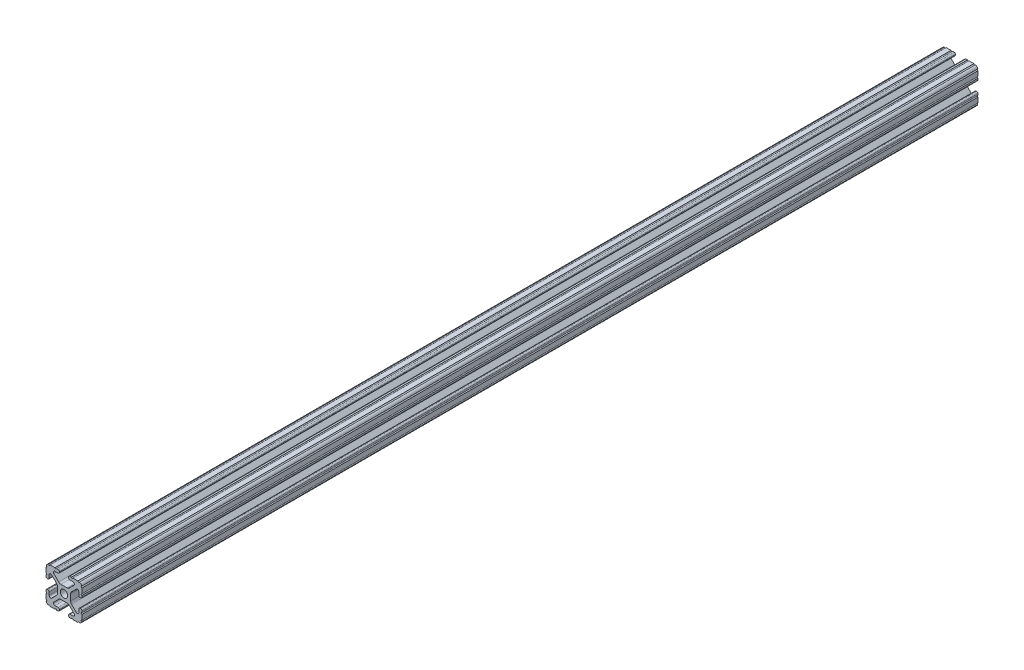
SolidWorks part; units mm, degrees
ref_plane "Front Plane" through (0, 0, 0) normal (0, 0, 1) x (1, 0, 0)
ref_plane "Top Plane" through (0, 0, 0) normal (0, 1, 0) x (1, 0, 0)
ref_plane "Right Plane" through (0, 0, 0) normal (1, 0, 0) x (0, 0, -1)
other "Configuration Table"
sketch "Sketch2" plane through (0, 0, 0) normal (0, 0, 1) x (1, 0, 0)
  line L0 (0, 12.7) -> (0, -12.7) construction
  line L1 (-12.7, 0) -> (12.7, 0) construction
  line L2 (3.2512, -12.7) -> (12.7, -12.7)
  line L3 (12.7, -12.7) -> (12.7, -3.2512)
  line L4 (3.2512, -12.7) -> (3.2512, -10.4902)
  line L5 (3.2512, -10.4902) -> (8.9276, -10.4902)
  line L6 (8.9276, -10.4902) -> (3.0856, -4.6482)
  line L7 (0, 0) -> (12.7, -12.7) construction
  line L8 (12.7, -3.2512) -> (10.4902, -3.2512)
  line L9 (10.4902, -3.2512) -> (10.4902, -8.9276)
  line L10 (10.4902, -8.9276) -> (4.6482, -3.0856)
  circle A0 centre (0, 0) radius 2.6035
  arc A1 (6.3485, -10.4902) -> (7.1039, -8.6665) centre (6.3485, -9.4219) ccw construction
  point P8 (0, -4.6482)
  dimension "Center Hole Diameter" = 5.207
  dimension "Rail Height" = 25.4
  dimension "Rail Width" = 25.4
  dimension "T-Slot Width" = 6.5024
  dimension "Slot Inner Width" = 14.8336
  dimension "Thickness" = 2.2098
  dimension "Slot Depth" = 5.842
  dimension "D1" = 2.2098
sketch "Sketch3" plane through (0, 0, 0) normal (1, 0, 0) x (0, 0, -1)
  line L0 (-316.5, -12.7) -> (316.5, -12.7) construction
  line L1 (-291.1, 0) -> (291.1, 0) construction
  dimension "Length" = 633
  dimension "D1" = 25.4
sketch "Sketch4" plane through (0, 0, 0) normal (0, 0, 1) x (1, 0, 0)
  line L0 (4.1904, -12.7) -> (10.1173, -12.7)
  line L1 (3.2512, -12.7) -> (12.7, -12.7) construction
  line L2 (3.2512, -12.7) -> (3.2512, -10.4902) construction
  line L3 (3.2512, -10.4902) -> (8.9276, -10.4902) construction
  line L4 (3.2512, -11.4294) -> (3.2512, -11.7608)
  line L5 (4.1904, -10.4902) -> (6.3485, -10.4902)
  line L6 (0, -4.6482) -> (2.164, -4.6482)
  line L7 (8.9276, -10.4902) -> (3.0856, -4.6482) construction
  line L8 (3.7373, -5.2999) -> (7.1039, -8.6665)
  line L9 (12.7, -12.7) -> (12.7, -3.2512) construction
  line L10 (10.4902, -8.9276) -> (4.6482, -3.0856) construction
  line L11 (10.4902, -3.2512) -> (10.4902, -8.9276) construction
  line L12 (10.4902, -6.3485) -> (10.4902, -4.1904)
  line L13 (12.7, -3.2512) -> (10.4902, -3.2512) construction
  line L14 (11.4294, -3.2512) -> (11.7608, -3.2512)
  line L15 (12.7, -4.1904) -> (12.7, -10.1173)
  line L16 (8.6665, -7.1039) -> (5.2999, -3.7373)
  line L17 (4.6482, 0) -> (4.6482, -2.164)
  line L18 (-12.7, 0) -> (12.7, 0) construction
  line L19 (0, -4.6482) -> (0, -2.6035)
  line L20 (0, 12.7) -> (0, -12.7) construction
  line L21 (4.6482, 0) -> (2.6035, 0)
  arc A0 (3.2512, -11.7608) -> (4.1904, -12.7) centre (4.1904, -11.7608) ccw
  arc A2 (3.2512, -11.4294) -> (4.1904, -10.4902) centre (4.1904, -11.4294) cw
  arc A3 (6.3485, -10.4902) -> (7.1039, -8.6665) centre (6.3485, -9.4219) ccw
  arc A4 (2.164, -4.6482) -> (3.7373, -5.2999) centre (2.164, -6.8732) cw
  arc A5 (10.1173, -12.7) -> (12.7, -10.1173) centre (10.1173, -10.1173) ccw
  arc A6 (8.6665, -7.1039) -> (10.4902, -6.3485) centre (9.4219, -6.3485) ccw
  arc A7 (10.4902, -4.1904) -> (11.4294, -3.2512) centre (11.4294, -4.1904) cw
  arc A8 (11.7608, -3.2512) -> (12.7, -4.1904) centre (11.7608, -4.1904) cw
  arc A9 (5.2999, -3.7373) -> (4.6482, -2.164) centre (6.8732, -2.164) cw
  circle A10 centre (0, 0) radius 2.6035 construction
  arc A11 (0, -2.6035) -> (2.6035, 0) centre (0, 0) ccw
  dimension "D1" = 2.5827
  dimension "D2" = 2.225
  dimension "D3" = 0.9392
extrude "Boss-Extrude1" add sketch "Sketch4" along normal mid plane 633
sketch "Sketch5" plane through (0, 0, 0) normal (0, 0, 1) x (1, 0, 0)
  line L0 (3.2512, -12.7) -> (12.7, -12.7) construction
  line L1 (4.1904, -10.4902) -> (6.3485, -10.4902) construction
  line L3 (0, 0) -> (12.7, -12.7) construction
  line L4 (6.3485, -10.4902) -> (6.3485, -12.7) construction
  line L5 (8.9276, -10.4902) -> (3.0856, -4.6482) construction
  circle A0 centre (10.3562, -12.7) radius 0.5524
  circle A1 centre (5.796, -12.7) radius 0.5524
  circle A2 centre (12.7, -10.3562) radius 0.5524
  circle A3 centre (12.7, -5.796) radius 0.5524
  point P10 (5.2694, -10.4902)
  point P12 (9.4219, -6.3485)
  dimension "D1" = 1.1049
extrude "Cut-Extrude1" cut sketch "Sketch5" against normal through all both and the other way through all
mirror "Mirror1" about plane through (0, 0, 0) normal (1, 0, 0) of bodies 137 134
mirror "Mirror2" about plane through (0, 0, 0) normal (0, 1, 0) of bodies 135
equation "\"D1@Boss-Extrude1\"=\"Length@Sketch3\""
equation "\"D1@Sketch2\"=\"Thickness@Sketch2\""
equation "\"D2@Sketch4\"=\"Slot Inner Width@Sketch2\"*0.15"
equation "\"D1@Sketch4\"=\"D3@Sketch4\"*2.75"
equation "\"D3@Sketch4\"=\"Thickness@Sketch2\"*0.425"
equation "\"D1@Sketch5\"=\"Thickness@Sketch2\"*0.5"
